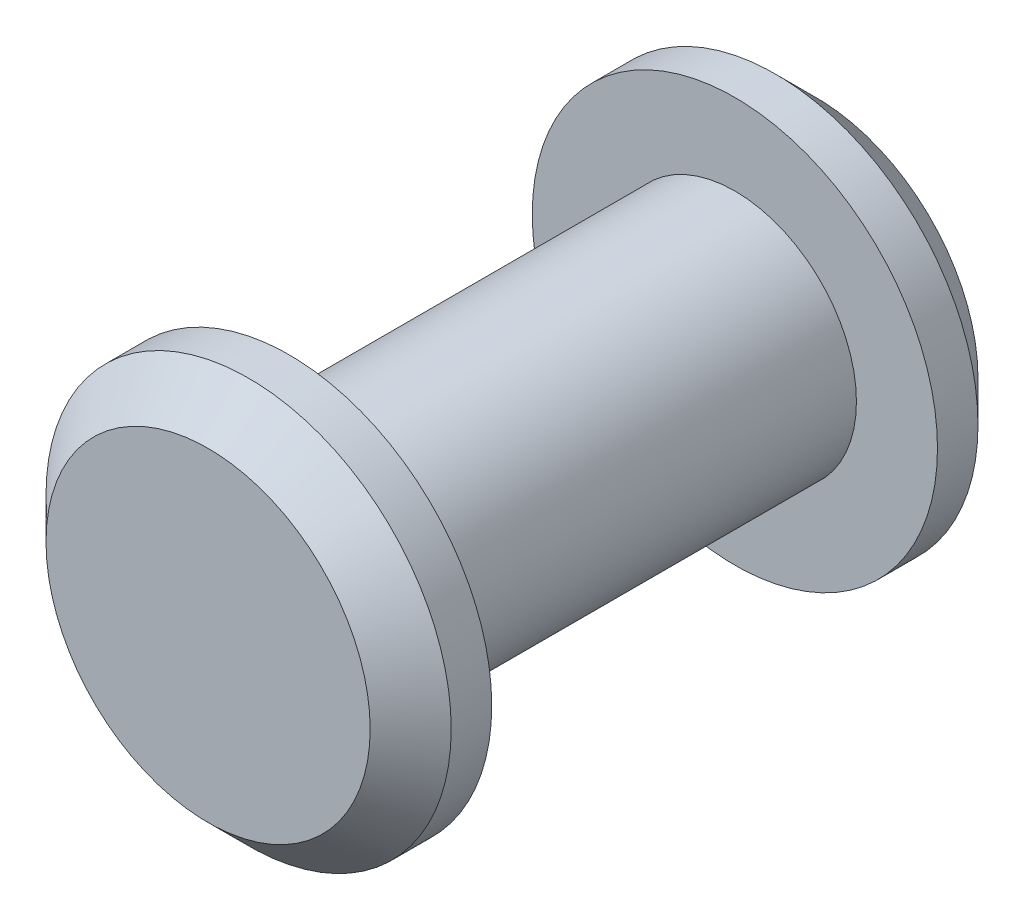
SolidWorks part; units mm, degrees
ref_plane "Front Plane" through (0, 0, 0) normal (0, 0, 1) x (1, 0, 0)
ref_plane "Top Plane" through (0, 0, 0) normal (0, 1, 0) x (1, 0, 0)
ref_plane "Right Plane" through (0, 0, 0) normal (1, 0, 0) x (0, 0, -1)
sketch "Sketch1" plane through (0, 0, 0) normal (0, 1, 0) x (1, 0, 0)
  line L0 (0, -15) -> (0, 15) construction
  line L1 (0, 15) -> (8, 15)
  line L2 (10, 13) -> (10, 11)
  line L3 (10, 11) -> (6, 11)
  line L4 (0, 15) -> (0, -15)
  line L5 (8, 15) -> (10, 13)
  line L6 (6, 11) -> (6, -11)
  line L7 (0, -15) -> (8, -15)
  line L8 (8, -15) -> (10, -13)
  line L9 (10, -13) -> (10, -11)
  line L10 (10, -11) -> (6, -11)
  point P4 (0, 0)
  point P5 (10, 15)
  point P10 (0, 0)
  point P11 (0, 0)
  point P14 (6, 11)
  dimension "D1" = 30
  dimension "D2" = 10
  dimension "D3" = 6
  dimension "D4" = 4
  dimension "D5" = 4
revolve "Revolve1" add sketch "Sketch1" angle 360 about L0
